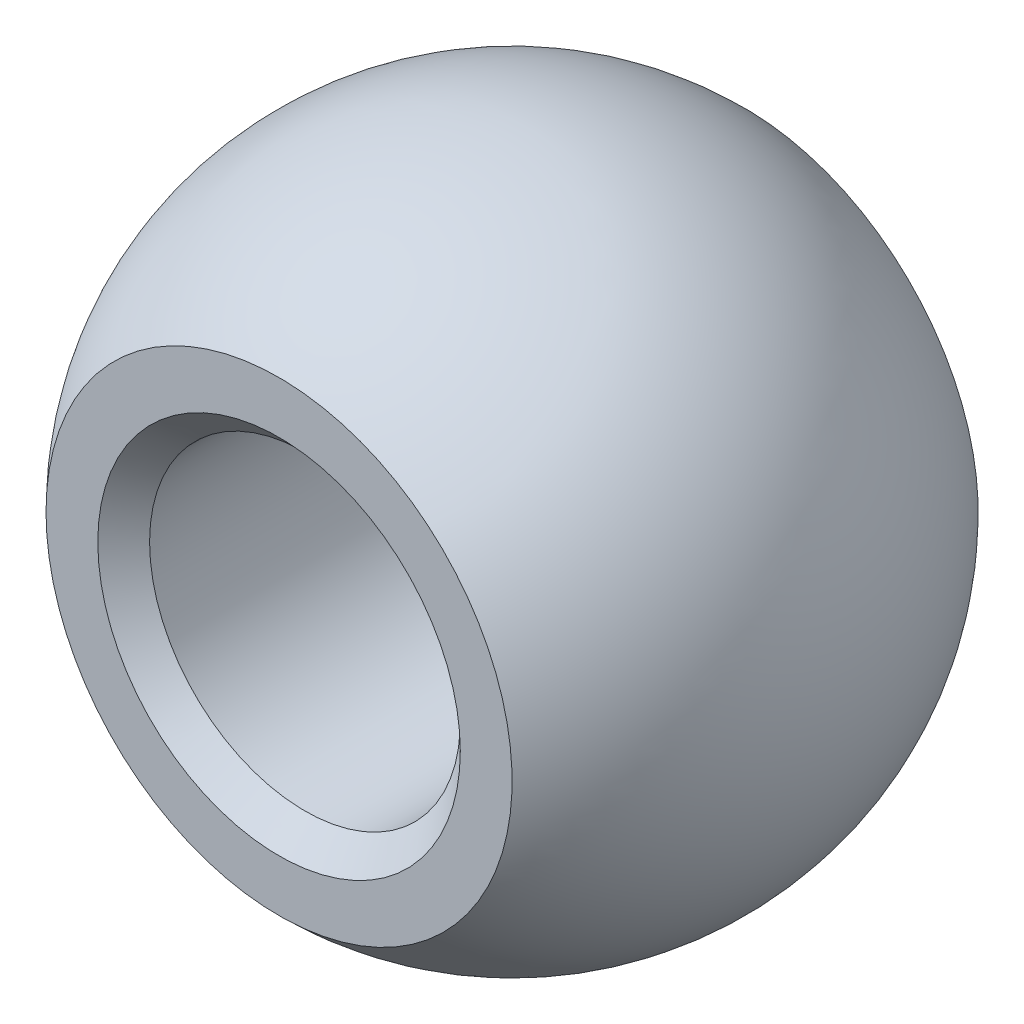
SolidWorks part; units mm, degrees
material "1.7035 (41Cr4)"
ref_plane "Płaszczyzna przednia" through (0, 0, 0) normal (0, 0, 1) x (1, 0, 0)
ref_plane "Płaszczyzna górna" through (0, 0, 0) normal (0, 1, 0) x (1, 0, 0)
ref_plane "Płaszczyzna prawa" through (0, 0, 0) normal (1, 0, 0) x (0, 0, -1)
sketch "Szkic2" plane through (0, 0, 0) normal (0, 0, 1) x (1, 0, 0)
  line L5 (-7, -7) -> (7, -7)
  line L6 (-7, -7) -> (-7, 7)
  line L7 (-7, 7) -> (7, 7)
  line L8 (7, -7) -> (7, 7)
  line L9 (-7, -7) -> (7, 7) construction
  line L10 (-7, 7) -> (7, -7) construction
  point P0 (0, 0)
  dimension "D1" = 14
extrude "Dodanie-wyciągnięcie1" add sketch "Szkic2" along normal mid plane 9
sketch "Szkic4" plane through (0, 0, 4.5) normal (0, 0, 1) x (1, 0, 0)
  line L0 (0, 4.5) -> (0, -4.5) construction
  circle A0 centre (0, 0) radius 4.5
  dimension "D1" = 9
sketch "Szkic5" plane through (0, 0, -4.5) normal (0, 0, -1) x (-1, 0, 0)
  line L0 (0, 4.5) -> (0, -4.5) construction
  circle A0 centre (0, 0) radius 4.5
  point P5 (0, 0)
  dimension "D1" = 9
sketch "Szkic6" plane through (0, 0, 0) normal (1, 0, 0) x (0, 0, -1)
  line L2 (0, -12.5743) -> (0, 12.8271) construction
  line L3 (0, 6.364) -> (0, 11.117)
  line L4 (0, 11.117) -> (-10.0136, 11.117)
  line L5 (-10.0136, 11.117) -> (-10.0136, -12.1123)
  line L6 (-10.0136, -12.1123) -> (0, -12.1123)
  line L7 (0, -12.1123) -> (0, -6.364)
  arc A0 (0, 6.364) -> (0, -6.364) centre (0, 0) ccw
  dimension "D1" = 12.7279
revolve "Wycięcie-obrót1" cut sketch "Szkic6" angle 360 about L2
sketch "Szkic7" plane through (0, 0, 0) normal (0, 0, 1) x (1, 0, 0)
  circle A0 centre (0, 0) radius 3
  dimension "D1" = 6
extrude "Wytnij-wyciągnięcie1" cut sketch "Szkic7" against normal through all both and the other way through all
chamfer "Sfazowanie1" distance 0.5 angle 45 2 edges at (3, 0, 4.5) (3, 0, -4.5)
